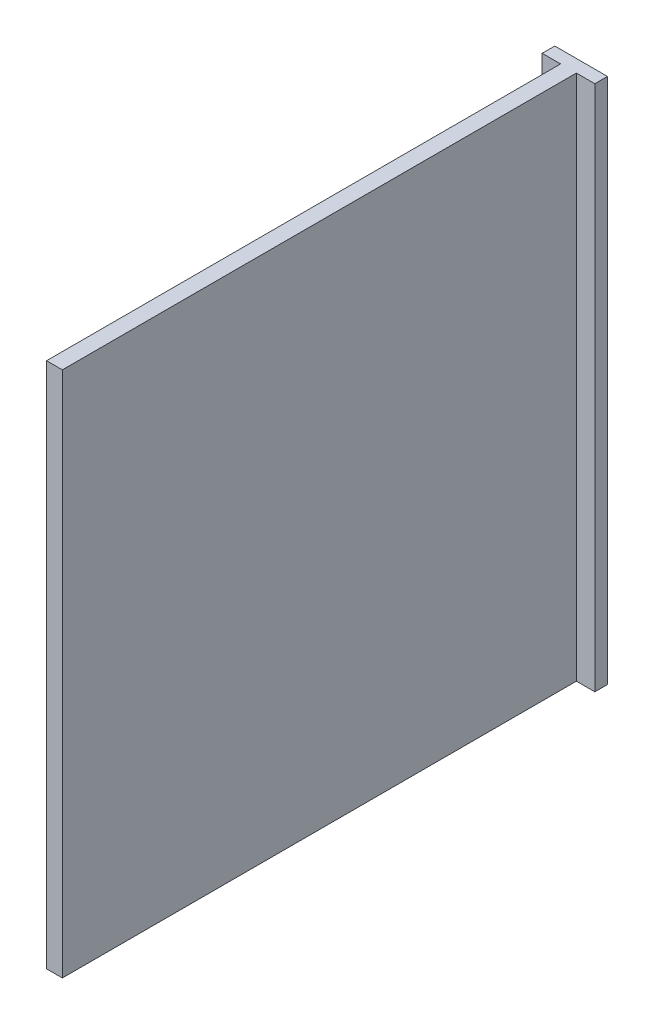
SolidWorks part; units mm, degrees
ref_plane "Front Plane" through (0, 0, 0) normal (0, 0, 1) x (1, 0, 0)
ref_plane "Top Plane" through (0, 0, 0) normal (0, 1, 0) x (1, 0, 0)
ref_plane "Right Plane" through (0, 0, 0) normal (1, 0, 0) x (0, 0, -1)
sketch "Sketch1" plane through (0, 0, 0) normal (0, 1, 0) x (1, 0, 0)
  line L0 (-1.25, 0) -> (1.25, 0)
  line L1 (1.25, 0) -> (1.25, -0.6)
  line L4 (-1.25, -0.6) -> (-1.25, 0)
  line L5 (0, 0) -> (0, -25) construction
  line L10 (-0.375, -25) -> (0.375, -25)
  line L12 (-1.25, -0.6) -> (-0.375, -0.6)
  line L13 (1.25, -0.6) -> (0.375, -0.6)
  line L15 (-0.375, -0.6) -> (-0.375, -25)
  line L16 (0.375, -25) -> (0.375, -0.6)
  point P4 (0, 0)
  point P12 (0, -0.75)
  point P16 (0, -0.75)
  dimension "D1" = 0.6
  dimension "D2" = 2.5
  dimension "D3" = 25
  dimension "D4" = 0.75
extrude "Boss-Extrude1" add sketch "Sketch1" along normal blind 25
